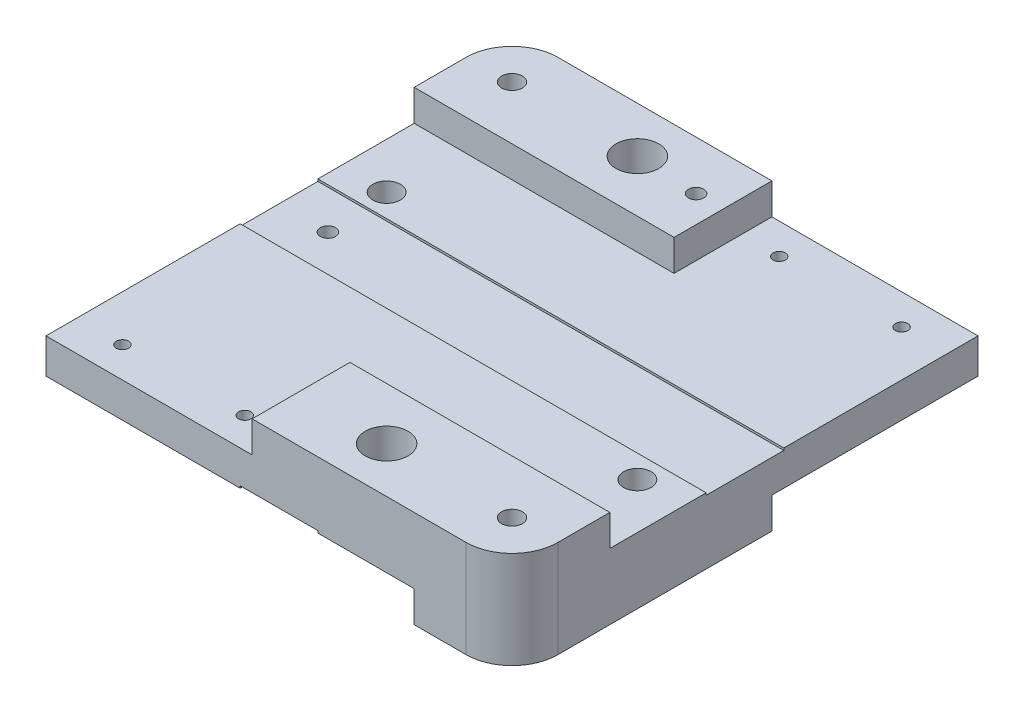
SolidWorks part; units mm, degrees
ref_plane "Front Plane" through (0, 0, 0) normal (0, 0, 1) x (1, 0, 0)
ref_plane "Top Plane" through (0, 0, 0) normal (0, 1, 0) x (1, 0, 0)
ref_plane "Right Plane" through (0, 0, 0) normal (1, 0, 0) x (0, 0, -1)
sketch "Sketch1" plane through (0, 0, 0) normal (0, 1, 0) x (1, 0, 0)
  line L1 (-76.2, -76.2) -> (76.2, -76.2)
  line L2 (-76.2, -76.2) -> (-76.2, 76.2)
  line L3 (-76.2, 76.2) -> (76.2, 76.2)
  line L4 (76.2, -76.2) -> (76.2, 76.2)
  line L5 (-76.2, -76.2) -> (76.2, 76.2) construction
  line L6 (-76.2, 76.2) -> (76.2, -76.2) construction
  point P0 (0, 0)
  dimension "D1" = 152.4
extrude "Boss-Extrude1" add sketch "Sketch1" along normal blind 11.4
sketch "Sketch2" plane through (0, 11.4, 0) normal (0, 1, 0) x (1, 0, 0)
  line L0 (0, 0) -> (61.7, 0) construction
  line L1 (61.7, 0) -> (61.7, -61.7) construction
  line L2 (76.2, -76.2) -> (76.2, 76.2) construction
  line L3 (-76.2, -76.2) -> (76.2, -76.2) construction
  line L4 (0, 0) -> (-61.7, 0) construction
  line L5 (-61.7, 0) -> (-61.7, 61.7) construction
  circle A0 centre (-61.7, 61.7) radius 0.5
  circle A1 centre (61.7, -61.7) radius 0.5
  dimension "D4" = 1
  dimension "D1" = 14.5
  dimension "D2" = 14.5
  dimension "D3" = 61.7
sketch "Sketch5" plane through (0, 11.4, 0) normal (0, 1, 0) x (1, 0, 0)
  line L1 (-76.2, 76.2) -> (8.8, 76.2)
  line L2 (-76.2, 76.2) -> (-76.2, 44.2)
  line L3 (-76.2, 44.2) -> (8.8, 44.2)
  line L4 (8.8, 76.2) -> (8.8, 44.2)
  line L5 (76.2, -76.2) -> (-8.8, -76.2)
  line L6 (76.2, -76.2) -> (76.2, -44.2)
  line L7 (76.2, -44.2) -> (-8.8, -44.2)
  line L8 (-8.8, -76.2) -> (-8.8, -44.2)
  dimension "D1" = 85
  dimension "D2" = 32
extrude "Boss-Extrude2" add sketch "Sketch5" along normal blind 10.2
sketch "Sketch6" plane through (0, 0, 0) normal (0, -1, 0) x (1, 0, 0)
  line L1 (76.2, 76.2) -> (44.2, 76.2)
  line L2 (76.2, 76.2) -> (76.2, -8.8)
  line L3 (76.2, -8.8) -> (44.2, -8.8)
  line L4 (44.2, 76.2) -> (44.2, -8.8)
  line L5 (-76.2, -76.2) -> (-44.2, -76.2)
  line L6 (-76.2, -76.2) -> (-76.2, 8.8)
  line L7 (-76.2, 8.8) -> (-44.2, 8.8)
  line L8 (-44.2, -76.2) -> (-44.2, 8.8)
  dimension "D1" = 85
  dimension "D2" = 32
extrude "Boss-Extrude3" add sketch "Sketch6" along normal blind 10.2
sketch "Sketch7" plane through (0, 0, 0) normal (0, -1, 0) x (1, 0, 0)
  line L1 (-12.7, 76.2) -> (12.7, 76.2)
  line L2 (-12.7, 76.2) -> (-12.7, -76.2)
  line L3 (-12.7, -76.2) -> (12.7, -76.2)
  line L4 (12.7, 76.2) -> (12.7, -76.2)
  line L6 (61.7, 0) -> (76.2, 0) construction
  line L7 (76.2, 76.2) -> (44.2, 76.2) construction
  line L8 (76.2, -76.2) -> (-44.2, -76.2) construction
  line L9 (-12.7, -76.2) -> (12.7, 76.2) construction
  dimension "D1" = 25.4
extrude "Cut-Extrude1" cut sketch "Sketch7" against normal blind 0.7
sketch "Sketch8" plane through (0, 11.4, 0) normal (0, 1, 0) x (1, 0, 0)
  line L0 (76.2, -44.2) -> (76.2, 76.2) construction
  line L1 (-76.2, 12.7) -> (76.2, 12.7)
  line L2 (-76.2, 12.7) -> (-76.2, -12.7)
  line L3 (-76.2, -12.7) -> (76.2, -12.7)
  line L4 (76.2, 12.7) -> (76.2, -12.7)
  line L6 (-76.2, 12.7) -> (76.2, -12.7) construction
  line L7 (-76.2, -12.7) -> (76.2, 12.7) construction
  dimension "D1" = 25.4
extrude "Cut-Extrude2" cut sketch "Sketch8" against normal blind 0.7
fillet "Fillet3" radius 15 2 edges at (-76.2, 5.7, -76.2) (76.2, 5.7, 76.2)
hole_wizard "M8x1.25 Tapped Hole2" positions "Sketch10" profile "Sketch9" tap size "M8x1.25" standard "ANSI Metric" end condition through all
sketch "Sketch10" plane through (0, -10.2, 0) normal (0, -1, 0) x (-1, 0, 0)
  point P0 (-61.7, -61.7)
  point P3 (61.7, 61.7)
cosmetic thread "Hole Thread3" parameters "D2"=8
cosmetic thread "Hole Thread4" parameters "D2"=8
sketch "Sketch9" plane through (61.7, -10.2, 61.7) normal (1, 0, 0) x (0, 0, -1)
  line L0 (0, 0) -> (0, 31.8)
  line L1 (0, 31.8) -> (3.4, 31.8)
  line L2 (3.4, 31.8) -> (3.4, 0)
  line L5 (3.4, 0) -> (0, 0)
  line L11 (0, -6.35) -> (0, 107.95) construction
  dimension "Thru Tap Drill Dia." = 6.8
  dimension "Thru Tap Drill Depth" = 31.8
sketch "Sketch11" plane through (0, 0, 0) normal (0, -1, 0) x (1, 0, 0)
  line L0 (-66.2, 82.1859) -> (-66.2, 8.8) construction
  line L1 (-76.2, 8.8) -> (-76.2, 76.2) construction
  line L3 (-76.2, 76.2) -> (-12.7, 76.2) construction
  line L4 (76.2, -76.2) -> (12.7, -76.2) construction
  line L5 (76.2, -8.8) -> (76.2, -76.2) construction
  line L8 (-44.2, 8.8) -> (-76.2, 8.8) construction
  line L11 (-76.2, 76.2) -> (-12.7, 76.2) construction
  circle A0 centre (-66.2, 61.2) radius 0.5
  circle A1 centre (-66.2, 21.2) radius 0.5
  circle A2 centre (66.2, -61.2) radius 0.5
  circle A3 centre (66.2, -21.2) radius 0.5
  dimension "D4" = 1
  dimension "D3" = 55
  dimension "D1" = 15
  dimension "D2" = 10
  dimension "D5" = 15
  dimension "D6" = 10
  dimension "D7" = 55
sketch "Sketch15" plane through (0, 11.4, 0) normal (0, 1, 0) x (1, 0, 0)
  line L0 (76.2, 12.7) -> (76.2, 76.2) construction
  line L1 (76.2, 76.2) -> (8.8, 76.2) construction
  line L2 (-76.2, -12.7) -> (-76.2, -76.2) construction
  line L3 (76.2, -44.2) -> (76.2, -12.7) construction
  line L6 (-76.2, -76.2) -> (-8.8, -76.2) construction
  circle A0 centre (61.2, 66.2) radius 0.5
  circle A1 centre (21.2, 66.2) radius 0.5
  circle A2 centre (-21.2, -66.2) radius 0.5
  circle A3 centre (-61.2, -66.2) radius 0.5
  dimension "D4" = 1
  dimension "D5" = 10
  dimension "D1" = 15
  dimension "D2" = 10
  dimension "D3" = 55
  dimension "D6" = 55
  dimension "D7" = 15
hole_wizard "#10-32 Tapped Hole3" positions "Sketch25" profile "Sketch24" tap size "#10-32" standard "ANSI Inch"
sketch "Sketch25" plane through (0, 11.4, 0) normal (0, 1, 0) x (1, 0, 0)
  point P0 (-21.2, -66.2)
  point P3 (-61.2, -66.2)
  point P6 (21.2, 66.2)
  point P9 (61.2, 66.2)
sketch "Sketch24" plane through (-21.2, 11.4, 66.2) normal (1, 0, 0) x (0, 0, 1)
  line L0 (0, 0) -> (0, 10.5933)
  line L1 (0, 10.5933) -> (2.0193, 9.38)
  line L2 (2.0193, 9.38) -> (2.0193, 0)
  line L5 (2.0193, 0) -> (0, 0)
  line L10 (0, 10.5933) -> (-2.0193, 9.38) construction
  line L11 (0, -6.35) -> (0, 107.95) construction
  dimension "Tap Drill Dia." = 4.0386
  dimension "Tap Drill Depth" = 9.38
  dimension "Drill Angle" = 118
cosmetic thread "Hole Thread13" parameters "D1"=7, "D2"=4.826
cosmetic thread "Hole Thread14" parameters "D1"=7, "D2"=4.826
cosmetic thread "Hole Thread15" parameters "D1"=7, "D2"=4.826
cosmetic thread "Hole Thread16" parameters "D1"=7, "D2"=4.826
hole_wizard "#10-32 Tapped Hole4" positions "Sketch27" profile "Sketch26" tap size "#10-32" standard "ANSI Inch"
sketch "Sketch27" plane through (0, 0, 0) normal (0, -1, 0) x (-1, 0, 0)
  point P0 (66.2, -61.2)
  point P3 (66.2, -21.2)
  point P6 (-66.2, 61.2)
  point P9 (-66.2, 21.2)
sketch "Sketch26" plane through (-66.2, 0, 61.2) normal (1, 0, 0) x (0, 0, -1)
  line L0 (0, 0) -> (0, 10.5933)
  line L1 (0, 10.5933) -> (2.0193, 9.38)
  line L2 (2.0193, 9.38) -> (2.0193, 0)
  line L5 (2.0193, 0) -> (0, 0)
  line L10 (0, 10.5933) -> (-2.0193, 9.38) construction
  line L11 (0, -6.35) -> (0, 107.95) construction
  dimension "Tap Drill Dia." = 4.0386
  dimension "Tap Drill Depth" = 9.38
  dimension "Drill Angle" = 118
cosmetic thread "Hole Thread17" parameters "D1"=7, "D2"=4.826
cosmetic thread "Hole Thread18" parameters "D1"=7, "D2"=4.826
cosmetic thread "Hole Thread19" parameters "D1"=7, "D2"=4.826
cosmetic thread "Hole Thread20" parameters "D1"=7, "D2"=4.826
sketch "Sketch28" plane through (0, 10.7, 0) normal (0, 1, 0) x (1, 0, 0)
  line L0 (-76.2, 0) -> (-60.2, 0) construction
  line L1 (-76.2, 12.7) -> (-76.2, -12.7) construction
  line L3 (-60.2, -12.7) -> (-60.2, 0) construction
  line L4 (-76.2, -12.7) -> (76.2, -12.7) construction
  line L5 (-60.2, 0) -> (-60.2, 12.7) construction
  line L6 (76.2, 12.7) -> (-76.2, 12.7) construction
  circle A0 centre (-60.2, 0) radius 0.25
  dimension "D2" = 0.5
  dimension "D1" = 16
hole_wizard "M6x1.0 Tapped Hole1" positions "Sketch30" profile "Sketch29" tap size "M6x1.0" standard "ANSI Metric" end condition through all
sketch "Sketch30" plane through (0, 10.7, 0) normal (0, 1, 0) x (1, 0, 0)
  point P0 (-60.2, 0)
sketch "Sketch29" plane through (-60.2, 10.7, 0) normal (1, 0, 0) x (0, 0, 1)
  line L0 (0, 0) -> (0, 20.9)
  line L1 (0, 20.9) -> (2.5, 20.9)
  line L2 (2.5, 20.9) -> (2.5, 0)
  line L5 (2.5, 0) -> (0, 0)
  line L11 (0, -6.35) -> (0, 107.95) construction
  dimension "Thru Tap Drill Dia." = 5
  dimension "Thru Tap Drill Depth" = 20.9
cosmetic thread "Hole Thread21" parameters "D2"=6
sketch "Sketch31" plane through (0, 0.7, 0) normal (0, -1, 0) x (1, 0, 0)
  line L0 (0, -76.2) -> (0, -60.2) construction
  line L1 (-12.7, -76.2) -> (12.7, -76.2) construction
  line L2 (0, -60.2) -> (12.7, -60.2) construction
  line L3 (12.7, -76.2) -> (12.7, 76.2) construction
  circle A0 centre (0, -60.2) radius 1.5
  dimension "D2" = 3
  dimension "D1" = 16
hole_wizard "M6x1.0 Tapped Hole2" positions "Sketch33" profile "Sketch32" tap size "M6x1.0" standard "ANSI Metric" end condition through all
sketch "Sketch33" plane through (0, 0.7, 0) normal (0, -1, 0) x (-1, 0, 0)
  point P0 (0, 60.2)
cosmetic thread "Hole Thread22" parameters "D2"=6
sketch "Sketch32" plane through (0, 0.7, -60.2) normal (1, 0, 0) x (0, 0, -1)
  line L0 (0, 0) -> (0, 20.9)
  line L1 (0, 20.9) -> (2.5, 20.9)
  line L2 (2.5, 20.9) -> (2.5, 0)
  line L5 (2.5, 0) -> (0, 0)
  line L11 (0, -6.35) -> (0, 107.95) construction
  dimension "Thru Tap Drill Dia." = 5
  dimension "Thru Tap Drill Depth" = 20.9
sketch "Sketch39" plane through (0, -10.2, 0) normal (0, -1, 0) x (1, 0, 0)
  line L0 (-61.2, -76.2) -> (-44.2, -76.2) construction
  line L1 (-76.2, 8.8) -> (-76.2, -61.2) construction
  line L2 (61.2, 76.2) -> (44.2, 76.2) construction
  line L3 (76.2, -8.8) -> (76.2, 61.2) construction
  circle A0 centre (-61.2, -20.2) radius 2.5
  circle A1 centre (61.2, 20.2) radius 2.5
  dimension "D1" = 56
  dimension "D2" = 15
  dimension "D3" = 5
  dimension "D4" = 56
  dimension "D6" = 5
  dimension "D5" = 15
hole_wizard "CBORE for M8 Hex Head Bolt3" positions "Sketch41" profile "Sketch40" counterbore size "M8" standard "ANSI Metric" end condition through all
sketch "Sketch41" plane through (0, -10.2, 0) normal (0, -1, 0) x (-1, 0, 0)
  point P0 (61.2, 20.2)
  point P3 (-61.2, -20.2)
sketch "Sketch40" plane through (-61.2, -10.2, -20.2) normal (1, 0, 0) x (0, 0, -1)
  line L0 (0, 0) -> (0, 31.8)
  line L1 (0, 31.8) -> (4.5, 31.8)
  line L3 (4.5, 31.8) -> (4.5, 10.18)
  line L4 (4.5, 10.18) -> (7, 10.18)
  line L5 (7, 10.18) -> (7, 0)
  line L7 (7, 0) -> (0, 0)
  line L11 (0, -6.35) -> (0, 107.95) construction
  dimension "Thru Hole Dia." = 9
  dimension "Thru Hole Depth" = 31.8
  dimension "C'Bore Dia." = 14
  dimension "C'Bore Depth" = 10.18
sketch "Sketch42" plane through (0, 21.6, 0) normal (0, 1, 0) x (1, 0, 0)
  line L0 (20.2, -61.2) -> (76.2, -61.2) construction
  line L1 (76.2, -61.2) -> (76.2, -44.2) construction
  line L2 (20.2, -61.2) -> (20.2, -76.2) construction
  line L3 (-8.8, -76.2) -> (61.2, -76.2) construction
  line L4 (-20.2, 61.2) -> (-76.2, 61.2) construction
  line L5 (-76.2, 61.2) -> (-76.2, 44.2) construction
  line L6 (-20.2, 61.2) -> (-20.2, 76.2) construction
  line L7 (8.8, 76.2) -> (-61.2, 76.2) construction
  circle A0 centre (20.2, -61.2) radius 2.5
  circle A1 centre (-20.2, 61.2) radius 2.5
  dimension "D1" = 5
  dimension "D2" = 56
  dimension "D3" = 15
hole_wizard "CBORE for M8 Hex Head Bolt4" positions "Sketch44" profile "Sketch43" counterbore size "M8" standard "ANSI Metric" end condition through all
sketch "Sketch44" plane through (0, 21.6, 0) normal (0, 1, 0) x (1, 0, 0)
  point P0 (-20.2, 61.2)
  point P3 (20.2, -61.2)
sketch "Sketch43" plane through (-20.2, 21.6, -61.2) normal (1, 0, 0) x (0, 0, 1)
  line L0 (0, 0) -> (0, 31.8)
  line L1 (0, 31.8) -> (4.5, 31.8)
  line L3 (4.5, 31.8) -> (4.5, 10.18)
  line L4 (4.5, 10.18) -> (7, 10.18)
  line L5 (7, 10.18) -> (7, 0)
  line L7 (7, 0) -> (0, 0)
  line L11 (0, -6.35) -> (0, 107.95) construction
  dimension "Thru Hole Dia." = 9
  dimension "Thru Hole Depth" = 31.8
  dimension "C'Bore Dia." = 14
  dimension "C'Bore Depth" = 10.18
